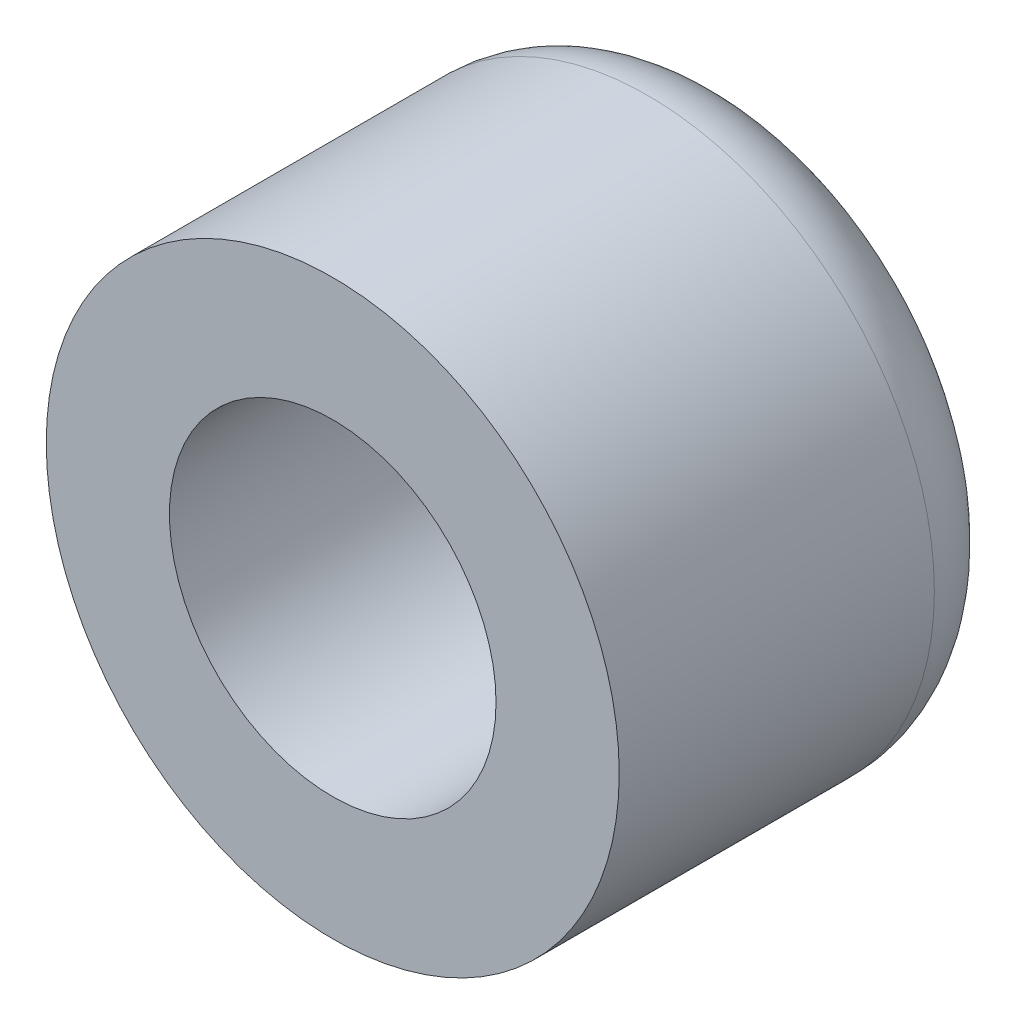
SolidWorks part; units mm, degrees
ref_plane "Front Plane" through (0, 0, 0) normal (1, 0, 0) x (0, 1, 0)
ref_plane "Top Plane" through (0, 0, 0) normal (0, 0, 1) x (0, 1, 0)
ref_plane "Right Plane" through (0, 0, 0) normal (0, 1, 0) x (-1, 0, 0)
sketch "Sketch1" plane through (0, 0, 0) normal (0, 0, 1) x (0, 1, 0)
  circle A0 centre (0, 0) radius 5
  dimension "D1" = 10
extrude "Boss-Extrude1" add sketch "Sketch1" along normal blind 7
sketch "Sketch2" plane through (0, 0, 7) normal (0, 0, 1) x (1, 0, 0)
  circle A0 centre (0, 0) radius 2.85
  dimension "D1" = 5.7
extrude "Cut-Extrude1" cut sketch "Sketch2" against normal blind 5.5
fillet "Fillet1" radius 1.5 1 edges at (5, 0, 0)
